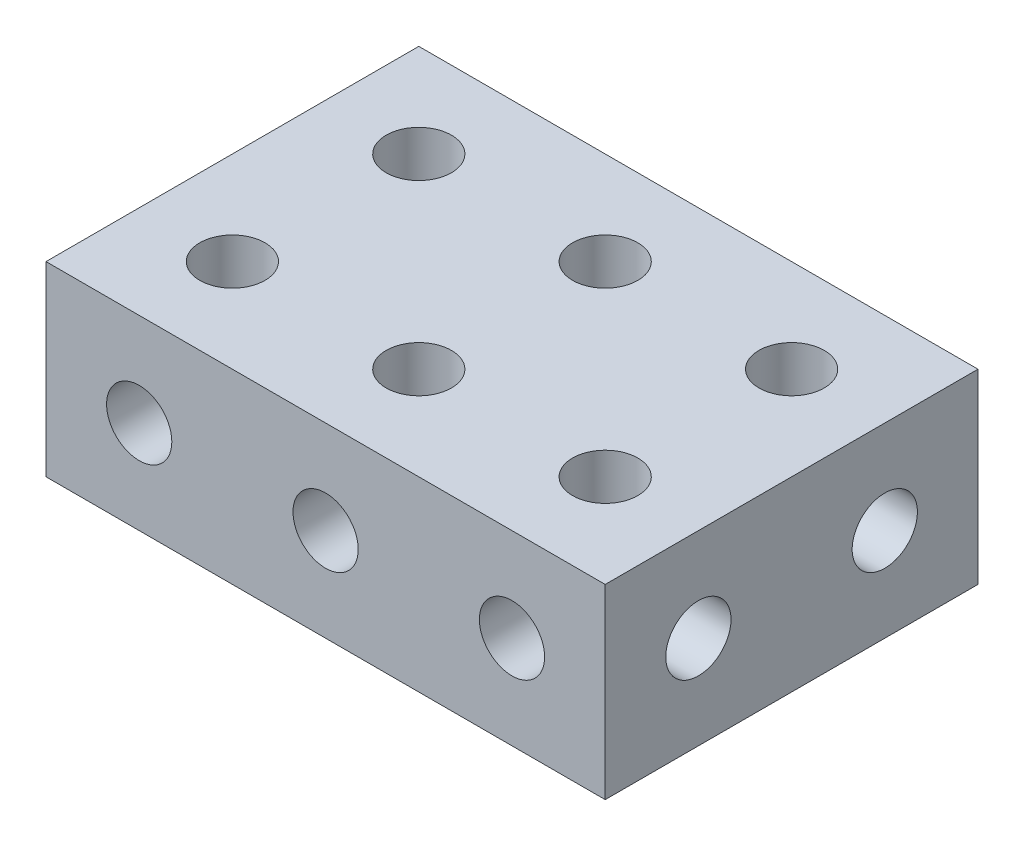
SolidWorks part; units mm, degrees
ref_plane "Plan de face" through (0, 0, 0) normal (0, 0, 1) x (1, 0, 0)
ref_plane "Plan de dessus" through (0, 0, 0) normal (0, 1, 0) x (1, 0, 0)
ref_plane "Plan de droite" through (0, 0, 0) normal (1, 0, 0) x (0, 0, -1)
sketch "Esquisse1" plane through (0, 0, 0) normal (1, 0, 0) x (0, 0, -1)
  line L1 (0, 0) -> (20, 0)
  line L2 (0, 0) -> (0, 10)
  line L3 (0, 10) -> (20, 10)
  line L4 (20, 0) -> (20, 10)
  dimension "D1" = 20
  dimension "D2" = 10
extrude "Boss.-Extru.1" add sketch "Esquisse1" along normal blind 30
sketch "Esquisse2" plane through (0, 10, 0) normal (0, 1, 0) x (1, 0, 0)
  line L0 (0, 15) -> (40, 15) construction
  line L4 (30, 20) -> (0, 20) construction
  circle A0 centre (5, 15) radius 1.75
  circle A1 centre (15, 15) radius 1.75
  circle A2 centre (25, 15) radius 1.75
  circle A3 centre (35, 15) radius 1.75
  circle A4 centre (5, 5) radius 1.75
  circle A5 centre (15, 5) radius 1.75
  circle A6 centre (25, 5) radius 1.75
  circle A7 centre (35, 5) radius 1.75
  circle A8 centre (5, -5) radius 1.75
  circle A9 centre (15, -5) radius 1.75
  circle A10 centre (25, -5) radius 1.75
  circle A11 centre (35, -5) radius 1.75
  circle A12 centre (5, -15) radius 1.75
  circle A13 centre (15, -15) radius 1.75
  circle A14 centre (25, -15) radius 1.75
  circle A15 centre (35, -15) radius 1.75
  dimension "D4" = 3.5
  dimension "D1" = 5
  dimension "D2" = 10
  dimension "D3" = 10
  dimension "D5" = 10
  dimension "D6" = 5
  dimension "D7" = 4
extrude "Enlèv. mat.-Extru.1" cut sketch "Esquisse2" against normal through all
sketch "Esquisse3" plane through (0, 0, 0) normal (0, 0, 1) x (1, 0, 0)
  line L0 (0, 5) -> (30, 5) construction
  line L1 (0, 10) -> (0, 0) construction
  line L2 (30, 10) -> (30, 0) construction
  circle A0 centre (5, 5) radius 1.75
  circle A1 centre (15, 5) radius 1.75
  circle A2 centre (25, 5) radius 1.75
  circle A3 centre (35, 5) radius 1.75
  dimension "D4" = 3.5
  dimension "D1" = 5
  dimension "D2" = 10
  dimension "D3" = 10
  dimension "D5" = 10
extrude "Enlèv. mat.-Extru.2" cut sketch "Esquisse3" against normal blind 40
sketch "Esquisse4" plane through (30, 0, 0) normal (1, 0, 0) x (0, 0, -1)
  line L0 (0, 5) -> (20, 5) construction
  line L1 (0, 10) -> (0, 0) construction
  line L2 (20, 0) -> (20, 10) construction
  circle A0 centre (5, 5) radius 1.75
  circle A1 centre (15, 5) radius 1.75
  circle A2 centre (25, 5) radius 1.75
  circle A3 centre (35, 5) radius 1.75
  dimension "D1" = 3.5
  dimension "D2" = 5
  dimension "D3" = 4
extrude "Enlèv. mat.-Extru.3" cut sketch "Esquisse4" against normal blind 40
